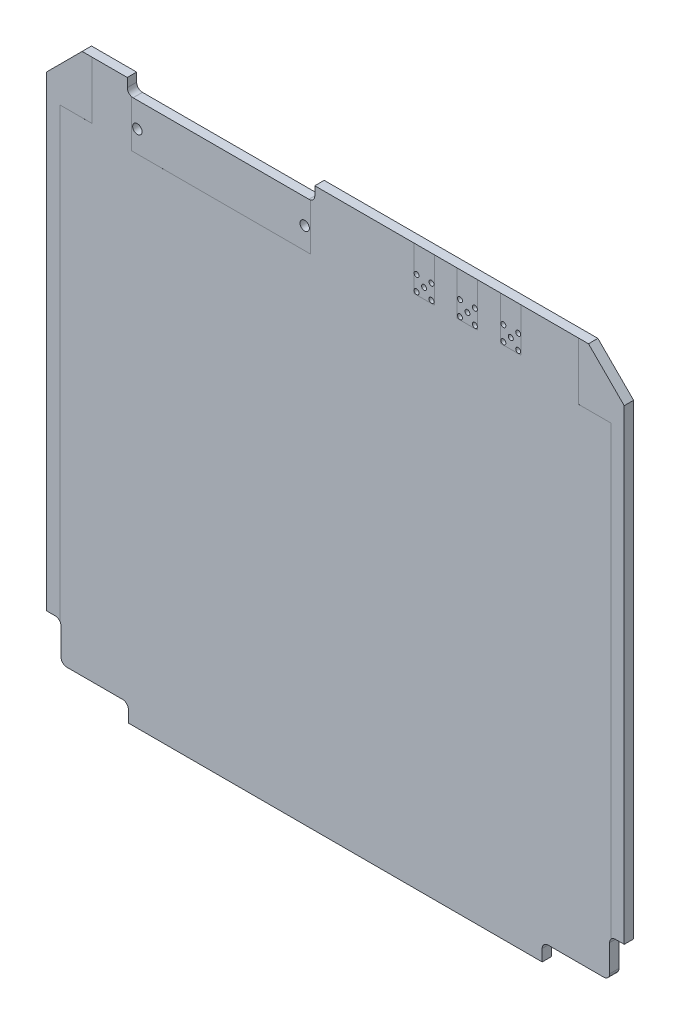
SolidWorks part; units mm, degrees
ref_plane "Front Plane" through (0, 0, 0) normal (0, 0, 1) x (1, 0, 0)
ref_plane "Top Plane" through (0, 0, 0) normal (0, 1, 0) x (1, 0, 0)
ref_plane "Right Plane" through (0, 0, 0) normal (1, 0, 0) x (0, 0, -1)
ref_plane "Plane4" through (0, 0, -0.0125) normal (0, 0, -1) x (-1, 0, 0)
sketch "Sketch1" plane through (0, 0, -0.0125) normal (0, 0, -1) x (-1, 0, 0)
  line L0 (35.3, -50) -> (35.3, -48)
  line L1 (36.3, -47) -> (45.8, -47)
  line L2 (46.8, -46) -> (46.8, -41.4)
  line L3 (47.8, -40.4) -> (49.3, -40.4)
  line L4 (49.3, -40.4) -> (49.3, 39.2)
  line L5 (49.3, 39.2) -> (43.2, 45.3)
  line L6 (43.2, 45.3) -> (35.5, 45.3)
  line L7 (35.5, 45.3) -> (35.5, 43.8)
  line L8 (34.5, 42.8) -> (4.5, 42.8)
  line L9 (3.5, 43.8) -> (3.5, 45.3)
  line L10 (3.5, 45.3) -> (-43.2, 45.3)
  line L11 (-43.2, 45.3) -> (-49.3, 39.2)
  line L12 (-49.3, 39.2) -> (-49.3, -40.4)
  line L13 (-49.3, -40.4) -> (-47.8, -40.4)
  line L14 (-46.8, -41.4) -> (-46.8, -46)
  line L15 (-45.8, -47) -> (-36.3, -47)
  line L16 (-35.3, -48) -> (-35.3, -50)
  line L17 (-35.3, -50) -> (35.3, -50)
  line L18 (0, -50) -> (0, 45.3) construction
  line L19 (19.5, 42.8) -> (19.5, 25.5258) construction
  line L20 (-13.87, 40.87) -> (-16.41, 38.33) construction
  line L21 (-21.27, 40.87) -> (-23.81, 38.33) construction
  line L22 (-28.67, 40.87) -> (-31.21, 38.33) construction
  arc A0 (35.3, -48) -> (36.3, -47) centre (36.3, -48) cw
  arc A1 (45.8, -47) -> (46.8, -46) centre (45.8, -46) ccw
  arc A2 (46.8, -41.4) -> (47.8, -40.4) centre (47.8, -41.4) cw
  arc A3 (35.5, 43.8) -> (34.5, 42.8) centre (34.5, 43.8) cw
  arc A4 (4.5, 42.8) -> (3.5, 43.8) centre (4.5, 43.8) cw
  arc A5 (-47.8, -40.4) -> (-46.8, -41.4) centre (-47.8, -41.4) cw
  arc A6 (-46.8, -46) -> (-45.8, -47) centre (-45.8, -46) ccw
  arc A7 (-36.3, -47) -> (-35.3, -48) centre (-36.3, -48) cw
  circle A8 centre (-21.27, 40.87) radius 0.425
  circle A9 centre (-23.81, 40.87) radius 0.425
  circle A10 centre (-22.54, 39.6) radius 0.425
  circle A11 centre (-13.87, 40.87) radius 0.425
  circle A12 centre (-23.81, 38.33) radius 0.425
  circle A13 centre (-16.41, 40.87) radius 0.425
  circle A14 centre (-15.14, 39.6) radius 0.425
  circle A15 centre (-21.27, 38.33) radius 0.425
  circle A16 centre (-28.67, 40.87) radius 0.425
  circle A17 centre (-31.21, 40.87) radius 0.425
  circle A18 centre (-16.41, 38.33) radius 0.425
  circle A19 centre (-29.94, 39.6) radius 0.425
  circle A20 centre (-31.21, 38.33) radius 0.425
  circle A21 centre (-28.67, 38.33) radius 0.425
  circle A22 centre (33.775, 38.54) radius 0.8
  circle A23 centre (5.225, 38.54) radius 0.8
  circle A24 centre (-13.87, 38.33) radius 0.425
  point P35 (-15.14, 39.6)
  dimension "D7" = 2.5
  dimension "D8" = 1.6
  dimension "D9" = 14.275
  dimension "D10" = 4.26
  dimension "D11" = 1
  dimension "D12" = 1
  dimension "D13" = 1
  dimension "D14" = 1
  dimension "D15" = 1
  dimension "D16" = 1
  dimension "D17" = 1
  dimension "D18" = 1
  dimension "D26" = 0.85
  dimension "D1" = 98.6
  dimension "D2" = 95.3
  dimension "D3" = 14
  dimension "D4" = 9.6
  dimension "D5" = 2.5
  dimension "D6" = 3
  dimension "D19" = 14
  dimension "D20" = 2.5
  dimension "D21" = 6.1
  dimension "D22" = 6.1
  dimension "D23" = 32
  dimension "D24" = 2.54
  dimension "D25" = 2.54
  dimension "D28" = 7.4
  dimension "D29" = 4.43
  dimension "D30" = 35.43
  dimension "D31" = 45
  dimension "D32" = 45
  dimension "D33" = 29.8
  dimension "D34" = 50
  dimension "D27" = 3
extrude "Boss-Extrude1" add sketch "Sketch1" against normal blind 1.6
sketch "thermalContacts_lower" plane through (0, 0, -0.0125) normal (0, 0, -1) x (-1, 0, 0)
  line L0 (47, 35.5) -> (47, -41.5) construction
  line L1 (41.5, 35.5) -> (41.5, 41.5) construction
  line L2 (41.5, 35.5) -> (47, 35.5) construction
  line L3 (47, 35.5) -> (47, -41.5)
  line L4 (41.5, 35.5) -> (41.5, 41.5)
  line L5 (41.5, 35.5) -> (47, 35.5)
  line L6 (-47, 35.5) -> (-47, -41.5) construction
  line L7 (-41.5, 35.5) -> (-47, 35.5) construction
  line L8 (-41.5, 35.5) -> (-41.5, 41.5) construction
  line L9 (-47, 35.5) -> (-47, -41.5)
  line L10 (-41.5, 35.5) -> (-47, 35.5)
  line L11 (-41.5, 35.5) -> (-41.5, 41.5)
  line L12 (-41.5, 41.5) -> (-41.5, 47) construction
  line L13 (-41.5, 41.5) -> (-49.5, 41.5) construction
  line L14 (-41.5, 41.5) -> (-41.5, 47)
  line L15 (-41.5, 41.5) -> (-49.5, 41.5) construction
  line L16 (41.5, 41.5) -> (41.5, 47) construction
  line L17 (41.5, 41.5) -> (49.5, 41.5) construction
  line L18 (41.5, 41.5) -> (41.5, 47)
  line L19 (41.5, 41.5) -> (49.5, 41.5) construction
  line L20 (47, -41.5) -> (59.8273, -41.5)
  line L21 (59.8273, -41.5) -> (59.8273, 47)
  line L22 (-56.1922, 47) -> (-41.5, 47)
  line L23 (41.5, 47) -> (59.8273, 47)
  line L24 (-56.1922, 47) -> (-56.1922, -41.5)
  line L25 (-47, -41.5) -> (-56.1922, -41.5)
sketch "thermalContacts_upper" plane through (0, 0, 1.5875) normal (0, 0, 1) x (1, 0, 0)
  line L3 (-47, 35.5) -> (-47, -41.5)
  line L4 (-41.5, 35.5) -> (-41.5, 41.5)
  line L5 (-41.5, 35.5) -> (-47, 35.5)
  line L9 (47, 35.5) -> (47, -41.5)
  line L10 (41.5, 35.5) -> (47, 35.5)
  line L11 (41.5, 35.5) -> (41.5, 41.5)
  line L14 (41.5, 41.5) -> (41.5, 47)
  line L15 (41.5, 41.5) -> (49.5, 41.5) construction
  line L18 (-41.5, 41.5) -> (-41.5, 47)
  line L19 (-41.5, 41.5) -> (-49.5, 41.5) construction
  line L20 (47, -41.5) -> (59.8273, -41.5)
  line L21 (59.8273, -41.5) -> (59.8273, 47)
  line L22 (59.8273, 47) -> (41.5, 47)
  line L23 (-41.5, 47) -> (-56.1922, 47)
  line L24 (-56.1922, 47) -> (-56.1922, -41.5)
  line L25 (-56.1922, -41.5) -> (-47, -41.5)
extrude "Cut-Extrude1" cut sketch "thermalContacts_lower" against normal blind 0.0001
extrude "Cut-Extrude2" cut sketch "thermalContacts_upper" against normal blind 0.0001
sketch "partFootprints" plane through (0, 0, 1.5875) normal (0, 0, 1) x (1, 0, 0)
  line L0 (-34.74, 34.84) -> (-34.74, 42.8292)
  line L1 (-4.26, 34.84) -> (-34.74, 34.84)
  line L2 (-41.5, 45.3) -> (-35.5, 45.3) construction
  line L3 (-36.1132, 45.3) -> (-39.5054, 45.3) construction
  line L4 (-4.26, 34.84) -> (-4.26, 42.8292)
  line L5 (-49.3, -40.4) -> (-49.3, 39.2) construction
  line L6 (13.39, 45.3) -> (13.39, 37.85)
  line L7 (13.39, 37.85) -> (16.89, 37.85)
  line L8 (16.89, 37.85) -> (16.89, 45.3)
  line L9 (16.89, 45.3) -> (13.39, 45.3)
  line L10 (20.79, 45.3) -> (20.79, 37.85)
  line L11 (20.79, 37.85) -> (24.29, 37.85)
  line L12 (24.29, 37.85) -> (24.29, 45.3)
  line L13 (24.29, 45.3) -> (20.79, 45.3)
  line L14 (28.19, 45.3) -> (28.19, 37.85)
  line L15 (28.19, 37.85) -> (31.69, 37.85)
  line L16 (31.69, 37.85) -> (31.69, 45.3)
  line L17 (31.69, 45.3) -> (28.19, 45.3)
  line L18 (49.3, -40.4) -> (49.3, 39.2) construction
  line L20 (-34.74, 42.8292) -> (-4.26, 42.8292)
  line L21 (-3.5, 45.3) -> (41.5, 45.3) construction
  arc A0 (-35.5, 43.8) -> (-34.5, 42.8) centre (-34.5, 43.8) ccw construction
  arc A1 (-4.5, 42.8) -> (-3.5, 43.8) centre (-4.5, 43.8) ccw construction
  dimension "D1" = 10.46
  dimension "D2" = 14.56
  dimension "D3" = 30.48
  dimension "D4" = 3.5
  dimension "D5" = 7.45
  dimension "D7" = 7.4
  dimension "D8" = 17.61
  dimension "D6" = 3
extrude "Cut-Extrude3" cut sketch "partFootprints" against normal blind 0.0001
